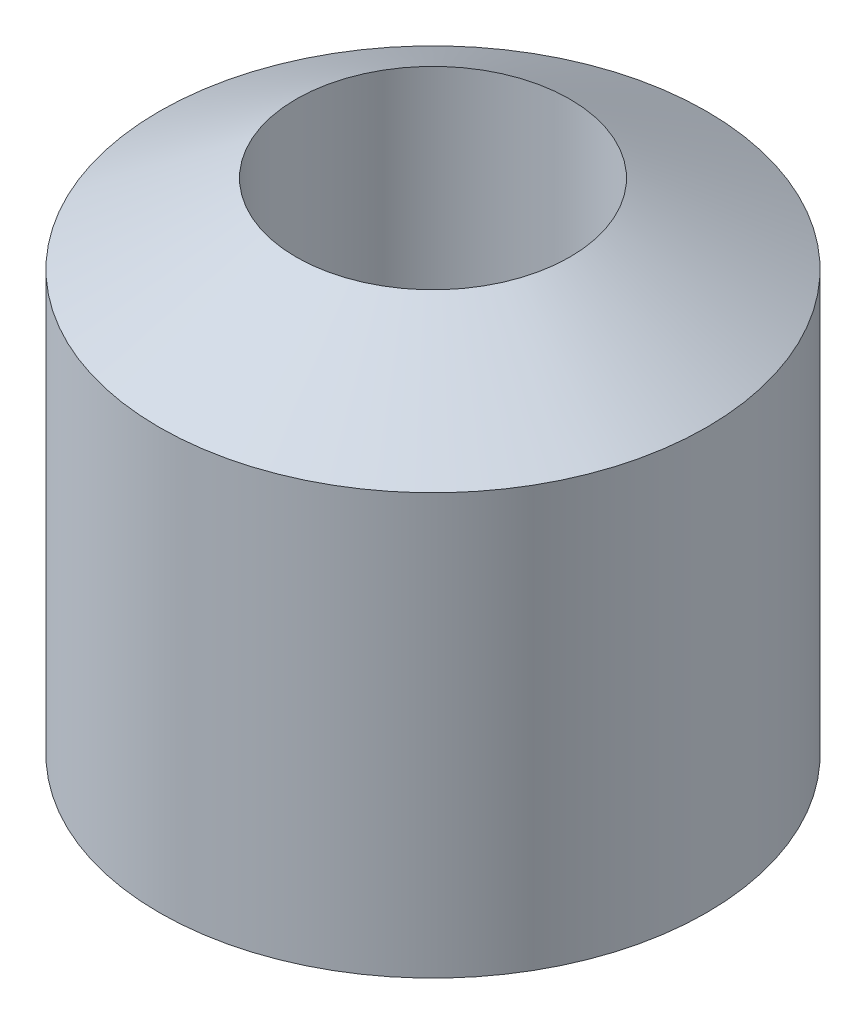
SolidWorks part; units mm, degrees
ref_plane "Front Plane" through (0, 0, 0) normal (0, 0, 1) x (1, 0, 0)
ref_plane "Top Plane" through (0, 0, 0) normal (0, 1, 0) x (1, 0, 0)
ref_plane "Right Plane" through (0, 0, 0) normal (1, 0, 0) x (0, 0, -1)
sketch "Sketch2" plane through (0, 0, 0) normal (0, 0, 1) x (1, 0, 0)
  line L0 (0, 0) -> (35.8105, 0) construction
  line L1 (0, 0) -> (0, 47.2452) construction
  line L2 (28, -21.5) -> (28, 21.5)
  line L3 (28, 21.5) -> (14, 29.5829)
  line L4 (14, 29.5829) -> (14, -29.5829)
  line L5 (28, -21.5) -> (14, -29.5829)
  point P9 (14, 0)
  point P10 (28, 0)
  dimension "D1" = 43
  dimension "D2" = 14
  dimension "D3" = 28
  dimension "D4" = 60
revolve "Revolve1" add sketch "Sketch2" angle 360 about L1
